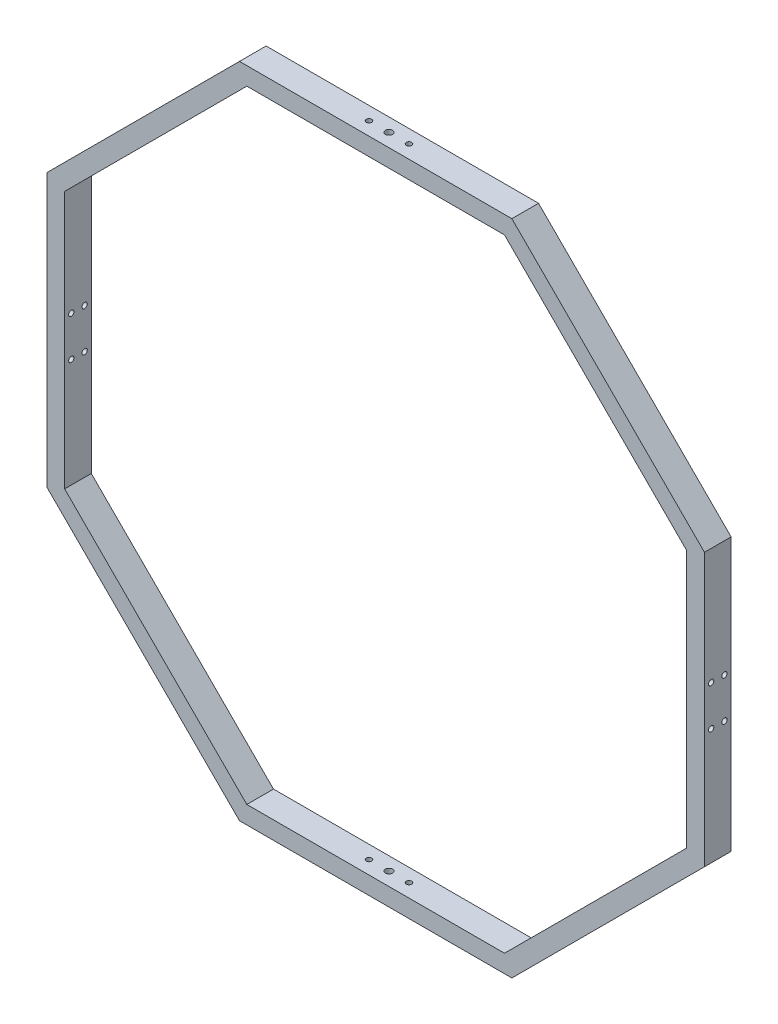
SolidWorks part; units mm, degrees
ref_plane "Front Plane" through (0, 0, 0) normal (0, 0, 1) x (1, 0, 0)
ref_plane "Top Plane" through (0, 0, 0) normal (0, 1, 0) x (1, 0, 0)
ref_plane "Right Plane" through (0, 0, 0) normal (1, 0, 0) x (0, 0, -1)
sketch "Sketch2" plane through (0, 0, 0) normal (0, 0, 1) x (1, 0, 0)
  line L0 (740, 306.518) -> (306.518, 740)
  line L1 (700, -289.9495) -> (700, 289.9495)
  line L2 (700, 289.9495) -> (289.9495, 700)
  line L3 (289.9495, 700) -> (-289.9495, 700)
  line L4 (-289.9495, 700) -> (-700, 289.9495)
  line L5 (-700, 289.9495) -> (-700, -289.9495)
  line L6 (-700, -289.9495) -> (-289.9495, -700)
  line L7 (-289.9495, -700) -> (289.9495, -700)
  line L8 (289.9495, -700) -> (700, -289.9495)
  line L9 (306.518, 740) -> (-306.518, 740)
  line L10 (-306.518, 740) -> (-740, 306.518)
  line L11 (-740, 306.518) -> (-740, -306.518)
  line L12 (-740, -306.518) -> (-306.518, -740)
  line L13 (-306.518, -740) -> (306.518, -740)
  line L14 (306.518, -740) -> (740, -306.518)
  line L15 (740, -306.518) -> (740, 306.518)
  circle A0 centre (0, 0) radius 700 construction
  dimension "D1" = 1400
  dimension "D3" = 613.0361
  dimension "D4" = 579.899
  dimension "D2" = 40
extrude "Boss-Extrude1" add sketch "Sketch2" along normal blind 60
sketch "Sketch4" plane through (0, -740, 0) normal (0, -1, 0) x (1, 0, 0)
  line L0 (0, 0) -> (0, 60) construction
  line L1 (-306.518, 60) -> (306.518, 60) construction
  line L2 (306.518, 30) -> (-306.518, 30) construction
  line L3 (306.518, 60) -> (306.518, 0) construction
  line L4 (-306.518, 60) -> (-306.518, 0) construction
  circle A0 centre (0, 30) radius 8
  circle A1 centre (-45, 30) radius 6
  circle A2 centre (45, 30) radius 6
  dimension "D1" = 16
  dimension "D2" = 45
  dimension "D3" = 45
  dimension "D4" = 12
  dimension "D5" = 12
extrude "Cut-Extrude1" cut sketch "Sketch4" against normal blind 1968
sketch "Sketch6" plane through (740, 0, 0) normal (1, 0, 0) x (0, 0, -1)
  line L0 (0, -306.518) -> (0, 306.518) construction
  line L3 (-60, 0) -> (0, 0) construction
  line L4 (-60, -306.518) -> (-60, 306.518) construction
  circle A3 centre (-15, 45) radius 6
  circle A6 centre (-15, -45) radius 6
  circle A7 centre (-45, 45) radius 6
  circle A8 centre (-45, -45) radius 6
  dimension "D2" = 12
  dimension "D3" = 12
  dimension "D4" = 12
  dimension "D5" = 15
  dimension "D6" = 12
  dimension "D7" = 15
  dimension "D8" = 15
  dimension "D9" = 90
extrude "Cut-Extrude2" cut sketch "Sketch6" against normal blind 1968
